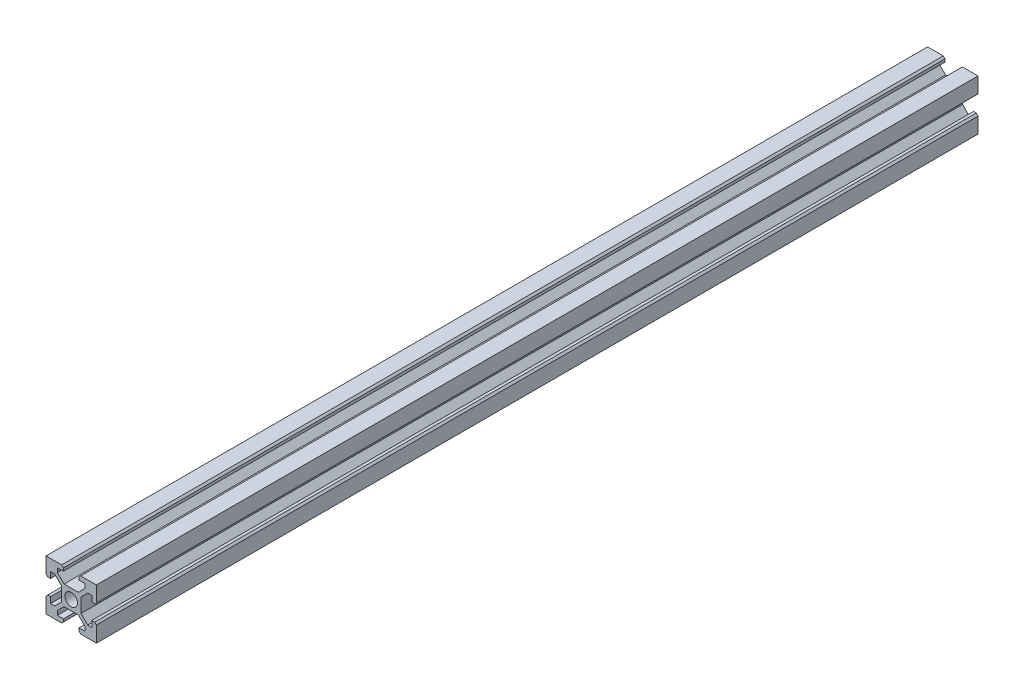
SolidWorks part; units mm, degrees
material "1060 Alloy"
ref_plane "Front Plane" through (0, 0, 0) normal (0, 0, 1) x (1, 0, 0)
ref_plane "Top Plane" through (0, 0, 0) normal (0, 1, 0) x (1, 0, 0)
ref_plane "Right Plane" through (0, 0, 0) normal (1, 0, 0) x (0, 0, -1)
sketch "Sketch1" plane through (0, 0, 0) normal (0, 0, 1) x (1, 0, 0)
  line L0 (3.9, -2.8393) -> (6.5607, -5.5)
  line L1 (-10, 10) -> (10, 10) construction
  line L2 (-10, 10) -> (-10, -10) construction
  line L3 (-10, -10) -> (10, -10) construction
  line L4 (10, 10) -> (10, -10) construction
  line L5 (-10, 10) -> (10, -10) construction
  line L6 (-10, -10) -> (10, 10) construction
  line L7 (-3.9, -3.9) -> (3.9, -3.9) construction
  line L8 (-3.9, -3.9) -> (-3.9, 3.9) construction
  line L9 (-3.9, 3.9) -> (3.9, 3.9) construction
  line L10 (3.9, -3.9) -> (3.9, 3.9) construction
  line L11 (-3.9, -3.9) -> (3.9, 3.9) construction
  line L12 (-3.9, 3.9) -> (3.9, -3.9) construction
  line L13 (-10, 10) -> (-5.5, 10) construction
  line L14 (-10, 10) -> (-10, 5.5) construction
  line L15 (-10, 5.5) -> (-5.5, 5.5) construction
  line L16 (-5.5, 10) -> (-5.5, 5.5) construction
  line L17 (10, 10) -> (5.5, 10) construction
  line L18 (10, 10) -> (10, 5.5) construction
  line L19 (10, 5.5) -> (5.5, 5.5) construction
  line L20 (5.5, 10) -> (5.5, 5.5) construction
  line L21 (-10, -10) -> (-5.5, -10) construction
  line L22 (-10, -10) -> (-10, -5.5) construction
  line L23 (-10, -5.5) -> (-5.5, -5.5) construction
  line L24 (-5.5, -10) -> (-5.5, -5.5) construction
  line L25 (10, -10) -> (5.5, -10) construction
  line L26 (10, -10) -> (10, -5.5) construction
  line L27 (10, -5.5) -> (5.5, -5.5) construction
  line L28 (5.5, -10) -> (5.5, -5.5) construction
  line L29 (2.8393, -3.9) -> (5.5, -6.5607)
  line L30 (-5.5, 6.5607) -> (-2.8393, 3.9)
  line L31 (-6.5607, 5.5) -> (-3.9, 2.8393)
  line L32 (5.5, 6.5607) -> (2.8393, 3.9)
  line L33 (6.5607, 5.5) -> (3.9, 2.8393)
  line L34 (-6.5607, -5.5) -> (-3.9, -2.8393)
  line L35 (-5.5, -6.5607) -> (-2.8393, -3.9)
  line L36 (-2.8393, 3.9) -> (2.8393, 3.9)
  line L37 (-3.9, 2.8393) -> (-3.9, -2.8393)
  line L38 (-2.8393, -3.9) -> (2.8393, -3.9)
  line L39 (3.9, -2.8393) -> (3.9, 2.8393)
  line L40 (5.5, 6.5607) -> (5.5, 8.2007)
  line L41 (5.5, 8.2007) -> (3.1, 8.2007)
  line L42 (3.1, 8.2007) -> (3.1, 9.3)
  line L43 (3.1, 9.3) -> (3.8, 10)
  line L44 (3.8, 10) -> (10, 10)
  line L45 (10, 10) -> (10, 3.8)
  line L46 (10, 3.8) -> (9.3, 3.1)
  line L47 (9.3, 3.1) -> (8.2007, 3.1)
  line L48 (8.2007, 3.1) -> (8.2007, 5.5)
  line L49 (8.2007, 5.5) -> (6.5607, 5.5)
  line L50 (3.1, -8.2007) -> (5.5, -8.2007)
  line L51 (3.1, -9.3) -> (3.1, -8.2007)
  line L52 (3.8, -10) -> (3.1, -9.3)
  line L53 (10, -10) -> (3.8, -10)
  line L54 (10, -3.8) -> (10, -10)
  line L55 (9.3, -3.1) -> (10, -3.8)
  line L56 (8.2007, -3.1) -> (9.3, -3.1)
  line L57 (8.2007, -5.5) -> (8.2007, -3.1)
  line L58 (6.5607, -5.5) -> (8.2007, -5.5)
  line L59 (5.5, -8.2007) -> (5.5, -6.5607)
  line L60 (-8.2007, -3.1) -> (-8.2007, -5.5)
  line L61 (-9.3, -3.1) -> (-8.2007, -3.1)
  line L62 (-10, -3.8) -> (-9.3, -3.1)
  line L63 (-10, -10) -> (-10, -3.8)
  line L64 (-3.8, -10) -> (-10, -10)
  line L65 (-3.1, -9.3) -> (-3.8, -10)
  line L66 (-3.1, -8.2007) -> (-3.1, -9.3)
  line L67 (-5.5, -8.2007) -> (-3.1, -8.2007)
  line L68 (-5.5, -6.5607) -> (-5.5, -8.2007)
  line L69 (-8.2007, -5.5) -> (-6.5607, -5.5)
  line L70 (-3.1, 8.2007) -> (-5.5, 8.2007)
  line L71 (-3.1, 9.3) -> (-3.1, 8.2007)
  line L72 (-3.8, 10) -> (-3.1, 9.3)
  line L73 (-10, 10) -> (-3.8, 10)
  line L74 (-10, 3.8) -> (-10, 10)
  line L75 (-9.3, 3.1) -> (-10, 3.8)
  line L76 (-8.2007, 3.1) -> (-9.3, 3.1)
  line L77 (-8.2007, 5.5) -> (-8.2007, 3.1)
  line L78 (-6.5607, 5.5) -> (-8.2007, 5.5)
  line L79 (-5.5, 8.2007) -> (-5.5, 6.5607)
  circle A0 centre (0, 0) radius 2.5
  point P83 (0, 0)
  dimension "D1" = 5
  dimension "D2" = 20
  dimension "D3" = 7.8
  dimension "D4" = 4.5
  dimension "D5" = 1.5
  dimension "D6" = 0.75
  dimension "D7" = 1.5
  dimension "D8" = 0.75
  dimension "D9" = 1.5
  dimension "D10" = 0.75
  dimension "D11" = 1.5
  dimension "D12" = 0.75
  dimension "D13" = 1.64
  dimension "D14" = 45
  dimension "D15" = 3.1
  dimension "D16" = 6.2
  dimension "D17" = 6.2
  dimension "D18" = 3.1
  dimension "D19" = 4
extrude "Boss-Extrude1" add sketch "Sketch1" along normal mid plane 350 contours L79 L70 L71 L72 L73 L74 L75 L76 L77 L78 L31 L37 L34 L69 L60 L61 L62 L63 L64 L65 L66 L67 L68 L35 L38 L29 L59 L50 L51 L52 L53 L54 L55 L56 L57 L58 L0 L39 L33 L49 L48 L47 L46 L45 L44 L43 L42 L41 L40 L32 L36
